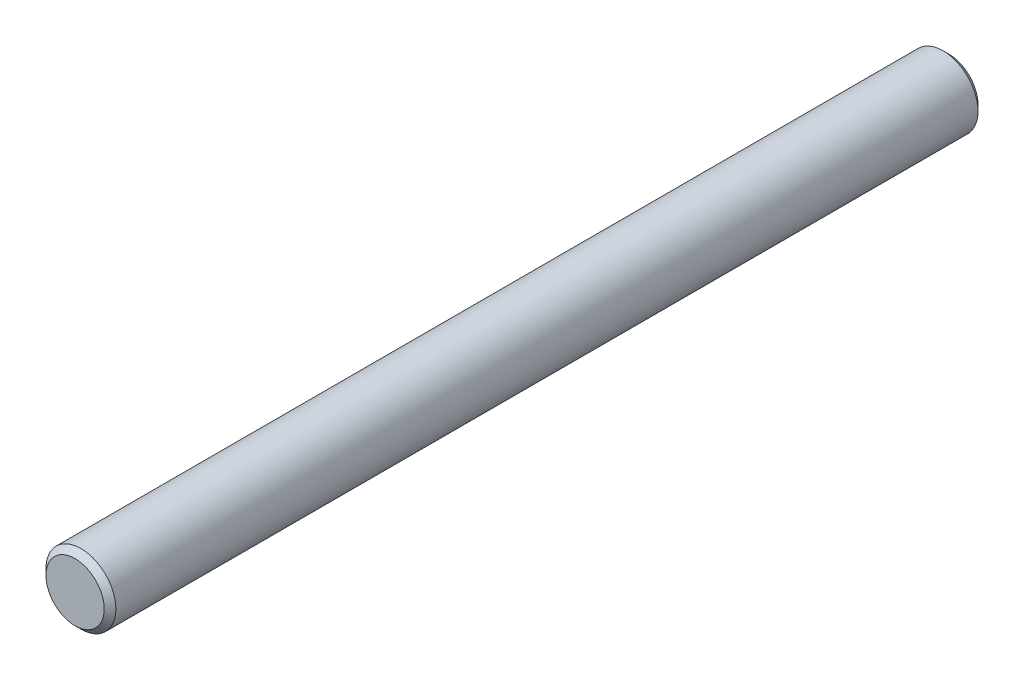
SolidWorks part; units mm, degrees
material "普通碳钢"
ref_plane "前视基准面" through (0, 0, 0) normal (0, 0, 1) x (1, 0, 0)
ref_plane "上视基准面" through (0, 0, 0) normal (0, 1, 0) x (1, 0, 0)
ref_plane "右视基准面" through (0, 0, 0) normal (1, 0, 0) x (0, 0, -1)
other "Configuration Table"
sketch "草图1" plane through (0, 0, 0) normal (0, 0, 1) x (1, 0, 0)
  circle A0 centre (0, 0) radius 3
  dimension "D1" = 6
extrude "凸台-拉伸1" add sketch "草图1" along normal mid plane 75
chamfer "倒角1" distance 0.5 angle 45 2 edges at (3, 0, 37.5) (3, 0, -37.5)
